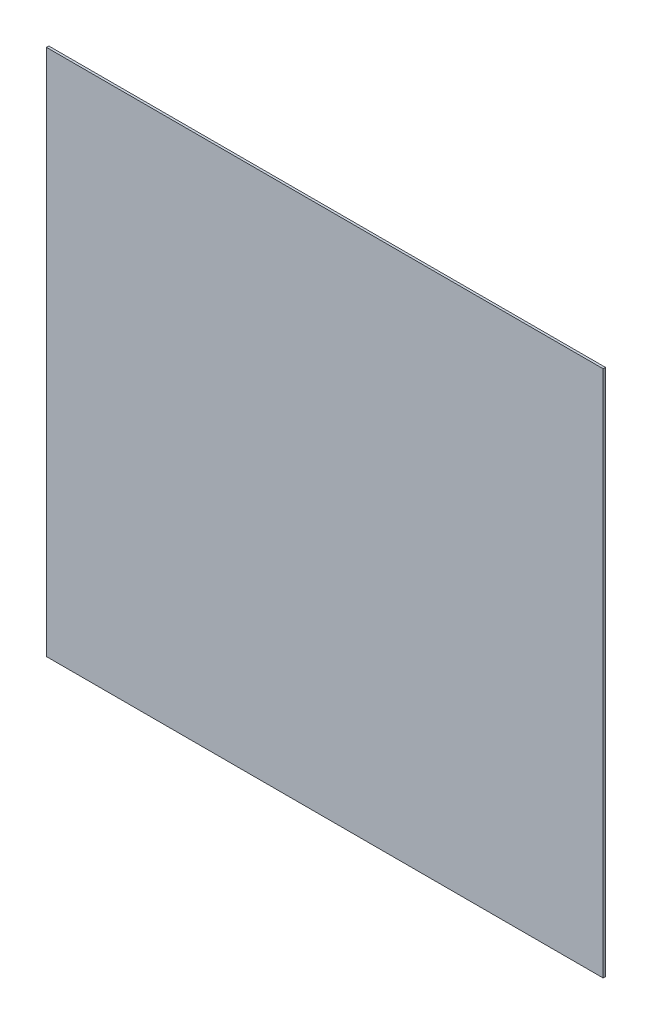
SolidWorks part; units mm, degrees
ref_plane "Alzado" through (0, 0, 0) normal (0, 0, 1) x (1, 0, 0)
ref_plane "Planta" through (0, 0, 0) normal (0, 1, 0) x (1, 0, 0)
ref_plane "Vista lateral" through (0, 0, 0) normal (1, 0, 0) x (0, 0, -1)
sketch "Croquis1" plane through (0, 0, 0) normal (0, 0, 1) x (1, 0, 0)
  line L1 (-560.475, -531.2625) -> (560.475, -531.2625)
  line L2 (-560.475, -531.2625) -> (-560.475, 531.2625)
  line L3 (-560.475, 531.2625) -> (560.475, 531.2625)
  line L4 (560.475, -531.2625) -> (560.475, 531.2625)
  line L5 (-560.475, -531.2625) -> (560.475, 531.2625) construction
  line L6 (-560.475, 531.2625) -> (560.475, -531.2625) construction
  point P0 (0, 0)
  dimension "D1" = 1120.95
  dimension "D2" = 1062.525
extrude "Saliente-Extruir1" add sketch "Croquis1" along normal blind 4.7625
